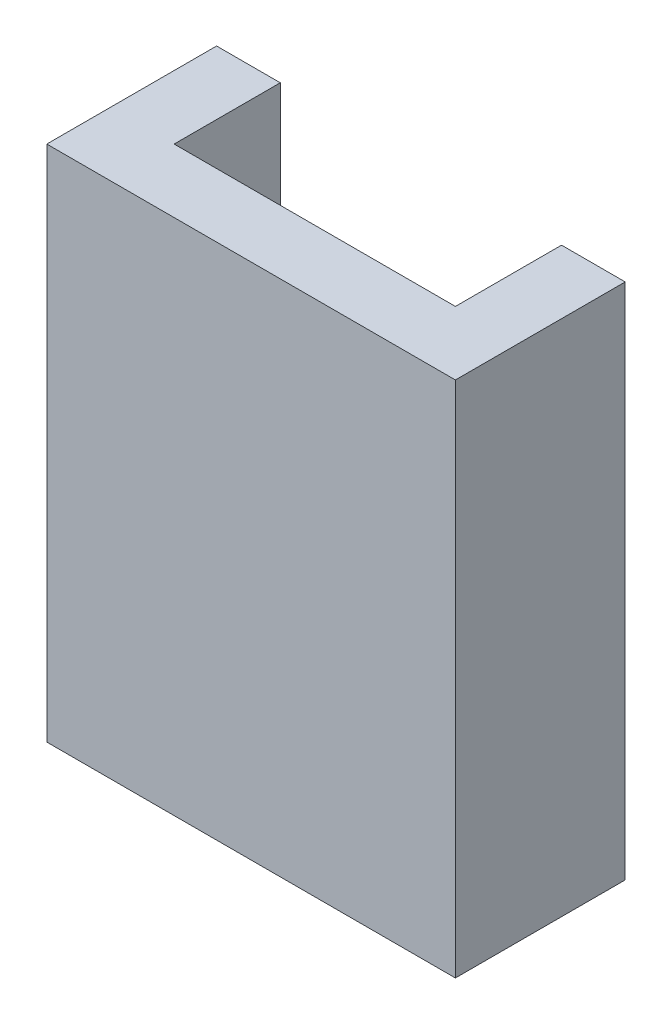
SolidWorks part; units mm, degrees
ref_plane "Front Plane" through (0, 0, 0) normal (0, 0, 1) x (1, 0, 0)
ref_plane "Top Plane" through (0, 0, 0) normal (0, 1, 0) x (1, 0, 0)
ref_plane "Right Plane" through (0, 0, 0) normal (1, 0, 0) x (0, 0, -1)
sketch "Sketch2" plane through (0, 0, 0) normal (0, 1, 0) x (1, 0, 0)
  line L0 (-9.625, 8) -> (9.625, 8)
  line L1 (-6.625, -5) -> (6.625, -5)
  line L2 (-6.625, -5) -> (-6.625, 5)
  line L3 (-6.625, 5) -> (6.625, 5)
  line L4 (6.625, -5) -> (6.625, 5)
  line L5 (-6.625, -5) -> (6.625, 5) construction
  line L6 (-6.625, 5) -> (6.625, -5) construction
  line L7 (9.625, -8) -> (9.625, 8)
  line L8 (-9.625, -8) -> (9.625, -8)
  line L9 (-9.625, -8) -> (-9.625, 8)
  line L10 (-9.625, 0) -> (9.625, 0)
  point P0 (0, 0)
  dimension "D1" = 10
  dimension "D2" = 13.25
  dimension "D3" = 3
extrude "Boss-Extrude1" add sketch "Sketch2" along normal blind 24.4 contours L10 L9 L8 L7 L4 L1 L2
